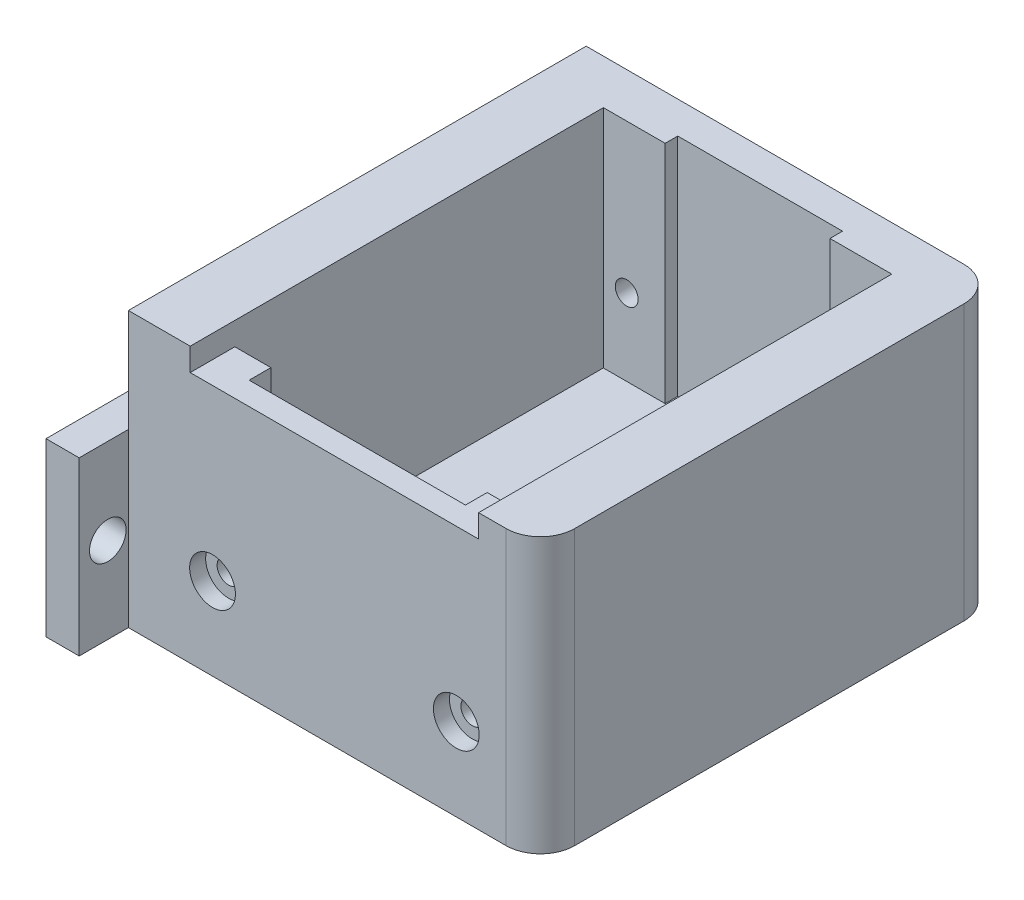
SolidWorks part; units mm, degrees
ref_plane "前视基准面" through (0, 0, 0) normal (0, 0, 1) x (1, 0, 0)
ref_plane "上视基准面" through (0, 0, 0) normal (0, 1, 0) x (1, 0, 0)
ref_plane "右视基准面" through (0, 0, 0) normal (1, 0, 0) x (0, 0, -1)
other "Configuration Table"
sketch "草图3" plane through (0, 0, 0) normal (0, 1, 0) x (1, 0, 0)
  line L1 (-18, -25) -> (18, -25)
  line L2 (-18, -25) -> (-18, 25)
  line L3 (-18, 25) -> (18, 25)
  line L4 (18, -25) -> (18, 25)
  line L5 (-18, -25) -> (18, 25) construction
  line L6 (-18, 25) -> (18, -25) construction
  point P0 (0, 0)
  dimension "D1" = 36
  dimension "D2" = 50
extrude "凸台-拉伸1" add sketch "草图3" along normal blind 24
sketch "草图4" plane through (0, 24, 0) normal (0, 1, 0) x (1, 0, 0)
  line L1 (-12.4, -15.9) -> (12.4, -15.9)
  line L2 (-12.4, -15.9) -> (-12.4, 15.9)
  line L3 (-12.4, 15.9) -> (12.4, 15.9)
  line L4 (12.4, -15.9) -> (12.4, 15.9)
  line L5 (-12.4, -15.9) -> (12.4, 15.9) construction
  line L6 (-12.4, 15.9) -> (12.4, -15.9) construction
  point P0 (0, 0)
  dimension "D1" = 24.8
  dimension "D2" = 31.8
extrude "切除-拉伸1" cut sketch "草图4" against normal blind 19.7
sketch "草图5" plane through (0, 24, 0) normal (0, 1, 0) x (1, 0, 0)
  line L0 (12.4, 15.9) -> (-12.4, 15.9) construction
  line L1 (-7, 14.8) -> (7, 14.8)
  line L2 (-7, 14.8) -> (-7, 17)
  line L3 (-7, 17) -> (7, 17)
  line L4 (7, 14.8) -> (7, 17)
  line L5 (-7, 14.8) -> (7, 17) construction
  line L6 (-7, 17) -> (7, 14.8) construction
  point P0 (0, 15.9)
  dimension "D1" = 14
  dimension "D2" = 2.2
extrude "切除-拉伸3" cut sketch "草图5" against normal blind 19.7 contours L3 L4 L1 L2
sketch "草图6" plane through (0, 24, 0) normal (0, 1, 0) x (1, 0, 0)
  line L0 (-12.4, -15.9) -> (12.4, -15.9) construction
  line L1 (-9.25, -17.8) -> (9.25, -17.8)
  line L2 (-9.25, -17.8) -> (-9.25, -14)
  line L3 (-9.25, -14) -> (9.25, -14)
  line L4 (9.25, -17.8) -> (9.25, -14)
  line L5 (-9.25, -17.8) -> (9.25, -14) construction
  line L6 (-9.25, -14) -> (9.25, -17.8) construction
  point P0 (0, -15.9)
  dimension "D1" = 18.5
  dimension "D2" = 3.8
extrude "切除-拉伸4" cut sketch "草图6" against normal blind 14.7
sketch "草图7" plane through (0, 24, 0) normal (0, 1, 0) x (1, 0, 0)
  line L0 (-18, -25) -> (18, -25) construction
  line L1 (-12.4, -37.1402) -> (12.4, -37.1402)
  line L2 (-12.4, -37.1402) -> (-12.4, -12.8598)
  line L3 (-12.4, -12.8598) -> (12.4, -12.8598)
  line L4 (12.4, -37.1402) -> (12.4, -12.8598)
  line L5 (-12.4, -37.1402) -> (12.4, -12.8598) construction
  line L6 (-12.4, -12.8598) -> (12.4, -37.1402) construction
  point P0 (0, -25)
  dimension "D1" = 24.8
extrude "切除-拉伸5" cut sketch "草图7" against normal blind 2
sketch "草图8" plane through (0, 0, 25) normal (0, 0, 1) x (1, 0, 0)
  line L0 (18, 24) -> (18, 0) construction
  line L1 (-18, 0) -> (18, 0) construction
  line L2 (-18, 24) -> (-18, 0) construction
  circle A0 centre (10.65, 7.2) radius 2
  circle A1 centre (-10.65, 7.2) radius 2
  dimension "D1" = 7.35
  dimension "D3" = 7.35
  dimension "D2" = 7.2
  dimension "D4" = 7.2
extrude "切除-拉伸6" cut sketch "草图8" against normal blind 6.4
sketch "草图9" plane through (0, 0, 18.6) normal (0, 0, 1) x (1, 0, 0)
  circle A0 centre (10.65, 7.2) radius 1
  circle A1 centre (-10.65, 7.2) radius 1
extrude "切除-拉伸7" cut sketch "草图9" against normal blind 6.4
sketch "草图10" plane through (0, 0, -25) normal (0, 0, -1) x (-1, 0, 0)
  line L0 (-18, 24) -> (-18, 0) construction
  line L1 (-18, 0) -> (18, 0) construction
  line L2 (18, 24) -> (18, 0) construction
  circle A0 centre (-10.565, 11) radius 2
  circle A1 centre (10.56, 11) radius 2
  dimension "D1" = 7.435
  dimension "D3" = 7.44
  dimension "D2" = 11
  dimension "D4" = 11
extrude "切除-拉伸8" cut sketch "草图10" against normal blind 7.4
sketch "草图11" plane through (0, 0, -17.6) normal (0, 0, -1) x (-1, 0, 0)
  circle A0 centre (10.56, 11) radius 1
  circle A1 centre (-10.565, 11) radius 1
extrude "切除-拉伸9" cut sketch "草图11" against normal blind 7.4
sketch "草图14" plane through (0, 0, 25) normal (0, 0, 1) x (1, 0, 0)
  line L1 (-26.5003, 33.3651) -> (21.1929, 33.3651)
  line L2 (-26.5003, 33.3651) -> (-26.5003, -8.5784)
  line L3 (-26.5003, -8.5784) -> (21.1929, -8.5784)
  line L4 (21.1929, 33.3651) -> (21.1929, -8.5784)
extrude "切除-拉伸12" cut sketch "草图14" against normal blind 4
sketch "草图16" plane through (0, 0, -25) normal (0, 0, -1) x (-1, 0, 0)
  line L1 (-33.7246, 32.2994) -> (35.4423, 32.2994)
  line L2 (-33.7246, 32.2994) -> (-33.7246, -7.1228)
  line L3 (-33.7246, -7.1228) -> (35.4423, -7.1228)
  line L4 (35.4423, 32.2994) -> (35.4423, -7.1228)
extrude "切除-拉伸13" cut sketch "草图16" against normal blind 5
sketch "草图18" plane through (0, 24, 0) normal (0, 1, 0) x (1, 0, 0)
  line L113 (-12.6, -16.1) -> (12.6, -16.1)
  line L114 (-12.6, 16.1) -> (-12.6, -16.1)
  line L115 (-7.2, 16.1) -> (-12.6, 16.1)
  line L116 (-7.2, 17.2) -> (-7.2, 16.1)
  line L117 (7.2, 17.2) -> (-7.2, 17.2)
  line L118 (7.2, 16.1) -> (7.2, 17.2)
  line L119 (12.6, 16.1) -> (7.2, 16.1)
  line L120 (12.6, -16.1) -> (12.6, 16.1)
  line L121 (-12.6, -16.1) -> (12.6, -16.1)
  line L122 (-12.6, 16.1) -> (-12.6, -16.1)
  line L123 (-7.2, 16.1) -> (-12.6, 16.1)
  line L124 (-7.2, 17.2) -> (-7.2, 16.1)
  line L125 (7.2, 17.2) -> (-7.2, 17.2)
  line L126 (7.2, 16.1) -> (7.2, 17.2)
  line L127 (12.6, 16.1) -> (7.2, 16.1)
  line L128 (12.6, -16.1) -> (12.6, 16.1)
  dimension "D1" = 0.2
extrude "切除-拉伸17" cut sketch "草图18" against normal blind 19.7
sketch "草图19" plane through (0, 22, 0) normal (0, 1, 0) x (1, 0, 0)
  line L14 (9.45, -18) -> (9.45, -15.9)
  line L15 (-9.45, -15.9) -> (-9.45, -18)
  line L16 (-9.45, -18) -> (9.45, -18)
  line L17 (9.45, -15.9) -> (-9.45, -15.9)
  line L18 (9.45, -18) -> (9.45, -15.9)
  line L19 (-9.45, -15.9) -> (-9.45, -18)
  line L20 (-9.45, -18) -> (9.45, -18)
  line L21 (9.45, -15.9) -> (-9.45, -15.9)
  dimension "D1" = 0.2
extrude "切除-拉伸18" cut sketch "草图19" against normal blind 12.7
sketch "草图21" plane through (-18, 0, 0) normal (-1, 0, 0) x (0, 0, 1)
  line L0 (-20, 0) -> (21, 0) construction
  line L1 (-24.5, 15) -> (-12.5, 15)
  line L2 (-24.5, 15) -> (-24.5, 0)
  line L3 (-24.5, 0) -> (-12.5, 0)
  line L4 (-12.5, 15) -> (-12.5, 0)
  line L6 (12.3, 0) -> (24.3, 0)
  line L7 (12.3, 0) -> (12.3, 15)
  line L8 (12.3, 15) -> (24.3, 15)
  line L9 (24.3, 0) -> (24.3, 15)
  dimension "D1" = 12
  dimension "D2" = 15
  dimension "D3" = 12.5
  dimension "D4" = 12
  dimension "D5" = 15
  dimension "D6" = 12.3
extrude "凸台-拉伸2" add sketch "草图21" along normal blind 2.9
sketch "草图23" plane through (-20.9, 0, 0) normal (-1, 0, 0) x (0, 0, 1)
  line L0 (-12.5, 15) -> (-24.5, 15) construction
  line L1 (-24.5, 15) -> (-24.5, 0) construction
  line L2 (24.3, 0) -> (24.3, 15) construction
  line L3 (24.3, 15) -> (12.3, 15) construction
  circle A0 centre (-22, 7.5) radius 1.6
  circle A1 centre (21.8, 7.5) radius 1.6
  dimension "D3" = 3.2
  dimension "D4" = 2.5
  dimension "D1" = 7.5
  dimension "D2" = 2.5
  dimension "D5" = 7.5
sketch "草图24" plane through (0, 0, 21) normal (0, 0, 1) x (1, 0, 0)
  line L1 (-18, 0) -> (22.9296, 0)
  line L2 (-18, 0) -> (-18, 30.0724)
  line L3 (-18, 30.0724) -> (22.9296, 30.0724)
  line L4 (22.9296, 0) -> (22.9296, 30.0724)
extrude "切除-拉伸20" cut sketch "草图24" against normal blind 1
extrude "切除-拉伸21" cut sketch "草图23" against normal blind 10
sketch "草图25" plane through (0, 24, 0) normal (0, 1, 0) x (1, 0, 0)
  line L1 (-12.6, 16.1) -> (12.6, 16.1)
  line L2 (-12.6, 16.1) -> (-12.6, -20.9995)
  line L3 (-12.6, -20.9995) -> (12.6, -20.9995)
  line L4 (12.6, 16.1) -> (12.6, -20.9995)
extrude "切除-拉伸22" cut sketch "草图25" against normal up to surface (2 mm away) up to face at (0, 22, 17.55)
fillet "圆角1" radius 3 2 edges at (18, 12, -20) (18, 12, 20)
